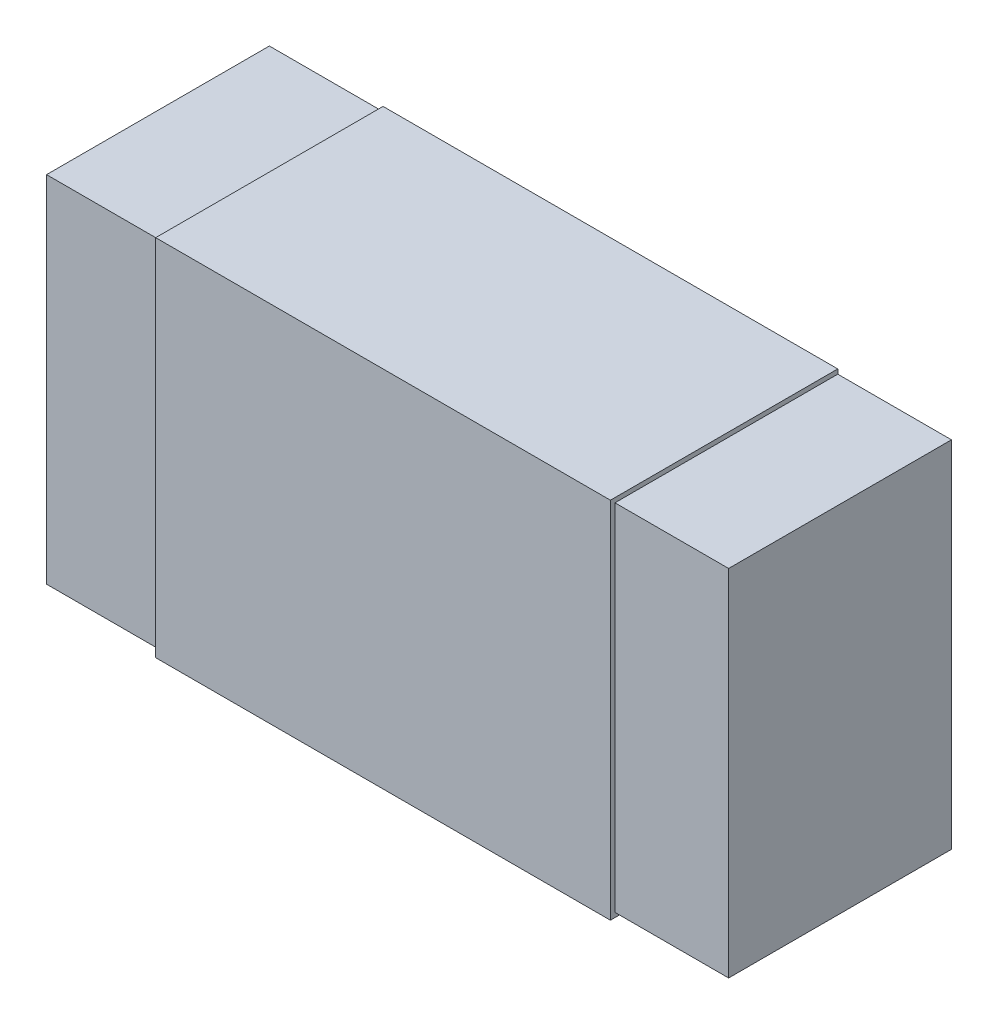
SolidWorks part; units mm, degrees
ref_plane "Front Plane" through (0, 0, 0) normal (0, 0, 1) x (1, 0, 0)
ref_plane "Top Plane" through (0, 0, 0) normal (0, 1, 0) x (1, 0, 0)
ref_plane "Right Plane" through (0, 0, 0) normal (1, 0, 0) x (0, 0, -1)
sketch "Sketch1" plane through (0, 0, 0) normal (0, 0, 1) x (1, 0, 0)
  line L1 (-0.5, 0.4) -> (0.5, 0.4)
  line L2 (-0.5, 0.4) -> (-0.5, -0.4)
  line L3 (-0.5, -0.4) -> (0.5, -0.4)
  line L4 (0.5, 0.4) -> (0.5, -0.4)
  line L5 (-0.5, 0.4) -> (0.5, -0.4) construction
  line L6 (-0.5, -0.4) -> (0.5, 0.4) construction
  point P0 (0, 0)
  dimension "D1" = 1
  dimension "D2" = 0.8
extrude "Boss-Extrude1" add sketch "Sketch1" along normal blind 0.5
sketch "Sketch4" plane through (0, 0, 0) normal (0, 0, -1) x (-1, 0, 0)
  line L0 (-0.5, -0.4) -> (-0.5, 0.4) construction
  line L1 (-0.5, 0.39) -> (-0.75, 0.39)
  line L2 (-0.5, 0.39) -> (-0.5, -0.39)
  line L3 (-0.5, -0.39) -> (-0.75, -0.39)
  line L4 (-0.75, 0.39) -> (-0.75, -0.39)
  line L5 (0.5, 0.4) -> (0.5, -0.4) construction
  line L6 (0.5, 0.39) -> (0.75, 0.39)
  line L7 (0.5, 0.39) -> (0.5, -0.39)
  line L8 (0.5, -0.39) -> (0.75, -0.39)
  line L9 (0.75, 0.39) -> (0.75, -0.39)
  line L10 (-0.5, 0.4) -> (0.5, 0.4) construction
  dimension "D1" = 0.25
  dimension "D2" = 0.25
  dimension "D3" = 0.78
  dimension "D4" = 0.78
  dimension "D5" = 0.01
  dimension "D6" = 0.01
extrude "Boss-Extrude3" add sketch "Sketch4" against normal blind 0.49
